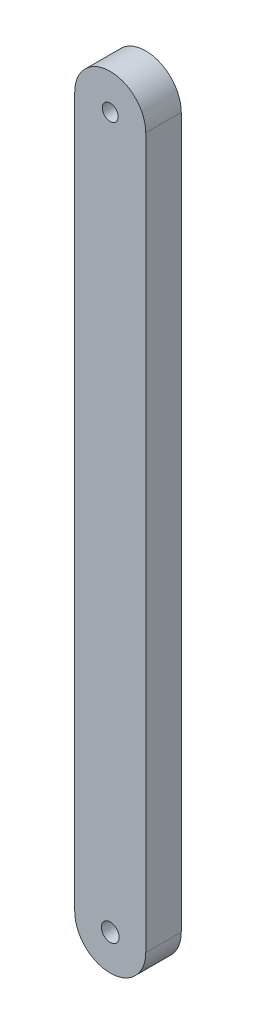
SolidWorks part; units mm, degrees
ref_plane "Front Plane" through (0, 0, 0) normal (0, 0, 1) x (1, 0, 0)
ref_plane "Top Plane" through (0, 0, 0) normal (0, 1, 0) x (1, 0, 0)
ref_plane "Right Plane" through (0, 0, 0) normal (1, 0, 0) x (0, 0, -1)
sketch "Sketch1" plane through (0, 0, 0) normal (0, 1, 0) x (1, 0, 0)
  line L0 (-10, 100) -> (10, 100) construction
  line L2 (10, -100) -> (10, 100)
  line L4 (-10, -100) -> (-10, 100)
  line L5 (10, -100) -> (-10, 100) construction
  line L6 (10, 100) -> (-10, -100) construction
  line L8 (-1.5875, 98.4125) -> (1.5875, 98.4125)
  line L9 (-1.5875, 98.4125) -> (-1.5875, 101.5875)
  line L10 (-1.5875, 101.5875) -> (1.5875, 101.5875)
  line L11 (1.5875, 98.4125) -> (1.5875, 101.5875)
  line L12 (-1.5875, 98.4125) -> (1.5875, 101.5875) construction
  line L13 (-1.5875, 101.5875) -> (1.5875, 98.4125) construction
  arc A0 (-10, 100) -> (10, 100) centre (0, 100) cw
  arc A1 (10, -100) -> (-10, -100) centre (0, -100) cw
  circle A2 centre (0, -100) radius 2.5
  circle A3 centre (0, 100) radius 2.2451
  point P0 (0, 0)
  dimension "D3" = 5
  dimension "D1" = 200
  dimension "D2" = 20
  dimension "D4" = 3.175
extrude "Boss-Extrude1" add sketch "Sketch1" along normal blind 10 contours A1 L2 A0 L4 A3 A2
move or copy body "Body-Move/Copy1" bodies to move or copy 101 copy no rotation origin (0, 5, 0) rotation axis (1, 0, 0) rotation angle 90
move or copy body "Body-Move/Copy2" bodies to move or copy 104 copy no translate (0, -105, 0)
